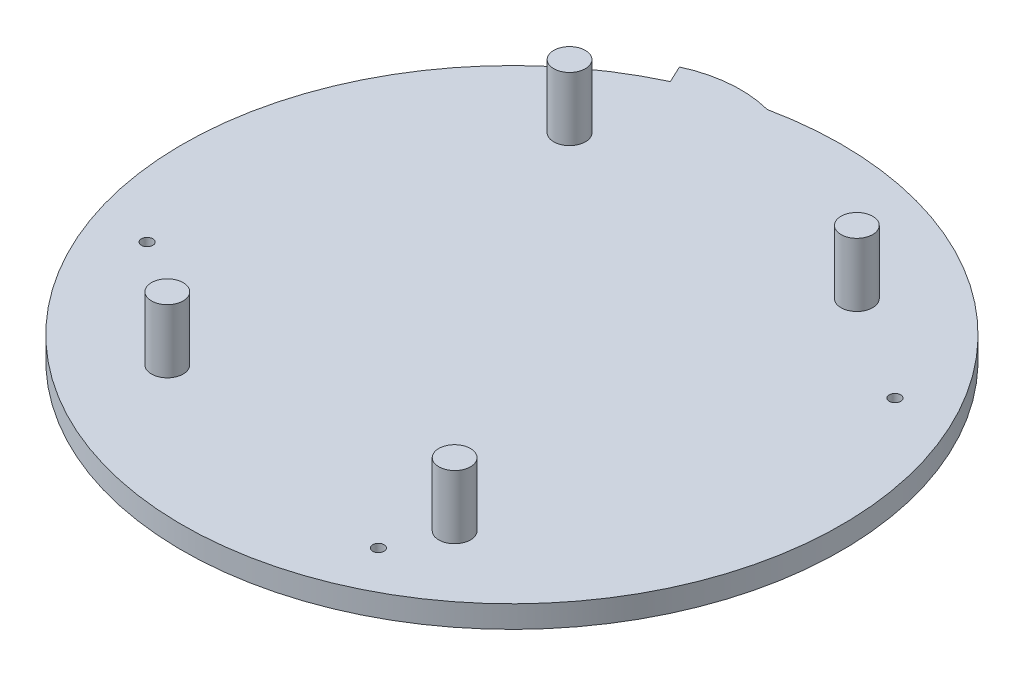
SolidWorks part; units mm, degrees
ref_plane "Front Plane" through (0, 0, 0) normal (0, 0, 1) x (1, 0, 0)
ref_plane "Top Plane" through (0, 0, 0) normal (0, 1, 0) x (1, 0, 0)
ref_plane "Right Plane" through (0, 0, 0) normal (1, 0, 0) x (0, 0, -1)
sketch "Sketch1" plane through (0, 0, 0) normal (0, 1, 0) x (1, 0, 0)
  line L1 (-21.7021, 46.6654) -> (-22.9762, 49.3813) construction
  line L2 (-21.7021, 46.6654) -> (-22.9762, 49.3813)
  arc A6 (-21.7021, 46.6654) -> (-10.2421, 50.4913) centre (0.3834, -0.4115) ccw
  arc A7 (-10.2421, 50.4913) -> (-22.9762, 49.3813) centre (-15.0554, 32.1111) ccw construction
  arc A8 (-10.2421, 50.4913) -> (-22.9762, 49.3813) centre (-15.0554, 32.1111) ccw
extrude "Boss-Extrude1" add sketch "Sketch1" along normal blind 3.5
sketch "Sketch2" plane through (0, 3.5, 0) normal (0, 1, 0) x (1, 0, 0)
  circle A0 centre (-41.0407, -16.5313) radius 0.9
  circle A1 centre (39.2591, 21.1402) radius 0.9
  dimension "D1" = 1.8
  dimension "D2" = 1.8
extrude "Cut-Extrude1" cut sketch "Sketch2" against normal through all
sketch "Sketch3" plane through (0, 3.5, 0) normal (0, 1, 0) x (1, 0, 0)
  circle A0 centre (-22.6617, 31.7263) radius 2.5
  circle A1 centre (22.6617, 31.7263) radius 2.5
  circle A2 centre (22.6617, -31.7263) radius 2.5
  circle A3 centre (-22.6617, -31.7263) radius 2.5
  point P0 (0, 0)
  dimension "D1" = 5
extrude "Boss-Extrude2" add sketch "Sketch3" along normal blind 10
sketch "Sketch4" plane through (0, 0, 0) normal (0, -1, 0) x (1, 0, 0)
  circle A0 centre (18.9958, 40.0855) radius 0.9
extrude "Cut-Extrude2" cut sketch "Sketch4" against normal blind 10
